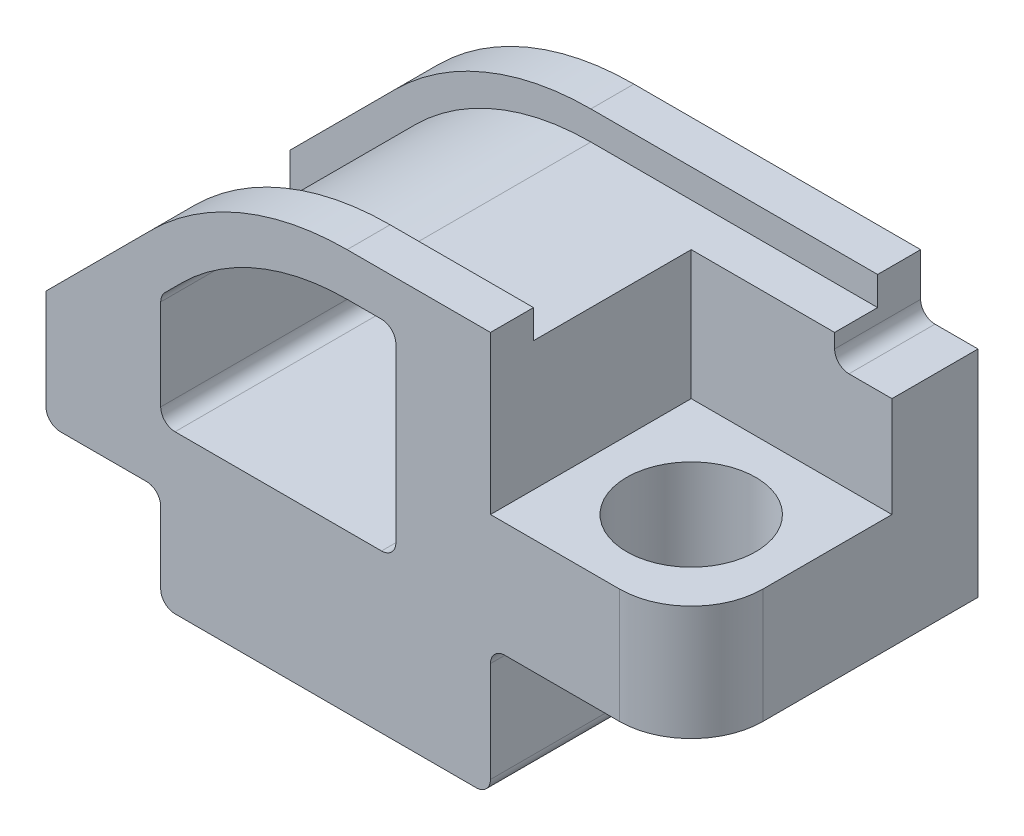
SolidWorks part; units mm, degrees
material "Copper"
ref_plane "Front Plane" through (0, 0, 0) normal (0, 0, 1) x (1, 0, 0)
ref_plane "Top Plane" through (0, 0, 0) normal (0, 1, 0) x (1, 0, 0)
ref_plane "Right Plane" through (0, 0, 0) normal (1, 0, 0) x (0, 0, -1)
sketch "Sketch1" plane through (0, 0, 0) normal (0, 0, 1) x (1, 0, 0)
  line L0 (0, 0) -> (-115, 0)
  line L1 (-115, 0) -> (-115, 35)
  line L2 (-115, 35) -> (-155, 35)
  line L3 (-155, 35) -> (-155, 75)
  line L5 (-50, 140) -> (50, 140)
  line L9 (70, 45) -> (0, 45)
  line L10 (0, 45) -> (0, 0)
  line L11 (-155, 75) -> (-118.2843, 111.7157)
  line L12 (70, 45) -> (70, 120)
  line L13 (70, 120) -> (50, 120)
  line L14 (50, 120) -> (50, 140)
  arc A0 (-50, 140) -> (-118.2843, 111.7157) centre (-50, 43.4315) ccw
  point P9 (60, 120)
  point P14 (17.1564, 142.4918)
  point P16 (-156.4116, 75)
  dimension "D1" = 115
  dimension "D2" = 35
  dimension "D3" = 40
  dimension "D4" = 45
  dimension "D8" = 70
  dimension "D9" = 45
  dimension "D5" = 100
  dimension "D6" = 20
  dimension "D7" = 75
  dimension "D10" = 140
  dimension "D11" = 225
extrude "Boss-Extrude1" add sketch "Sketch1" along normal mid plane 100
sketch "Sketch2" plane through (0, 0, 50) normal (0, 0, 1) x (1, 0, 0)
  line L0 (-33, 55) -> (-33, 125)
  line L1 (0, 0) -> (0, 45) construction
  line L17 (-115, 93.7868) -> (-115, 55)
  line L18 (-107.6777, 101.1091) -> (-144.3934, 64.3934)
  line L19 (-107.6777, 101.1091) -> (-115, 93.7868)
  line L20 (-115, 55) -> (-33, 55)
  line L24 (-115, 35) -> (-115, 0) construction
  line L25 (-50, 125) -> (-33, 125)
  arc A12 (-50, 125) -> (-107.6777, 101.1091) centre (-50, 43.4315) ccw
  arc A13 (-50, 125) -> (-107.6777, 101.1091) centre (-50, 43.4315) ccw
  dimension "D1" = 15
  dimension "D2" = 33
  dimension "D3" = 20
extrude "Cut-Extrude1" cut sketch "Sketch2" against normal through all both and the other way through all
sketch "Sketch3" plane through (0, 140, 0) normal (0, 1, 0) x (1, 0, 0)
  line L1 (70, -50) -> (0, -50)
  line L2 (70, -50) -> (70, 20)
  line L3 (70, 20) -> (0, 20)
  line L4 (0, -50) -> (0, 20)
  dimension "D1" = 70
extrude "Cut-Extrude2" cut sketch "Sketch3" against normal blind 55
sketch "Sketch4" plane through (0, 85, 0) normal (0, 1, 0) x (1, 0, 0)
  line L0 (70, -50) -> (70, 20) construction
  line L1 (0, -50) -> (70, -50) construction
  line L2 (35, -50) -> (35, 20) construction
  line L3 (70, 20) -> (0, 20) construction
  line L4 (70, -25) -> (70, -50)
  line L5 (70, -50) -> (45, -50)
  circle A0 centre (35, -15) radius 22.5
  arc A1 (45, -50) -> (70, -25) centre (45, -25) ccw
  point P5 (70, -15)
  dimension "D1" = 45
  dimension "D2" = 25
extrude "Cut-Extrude3" cut sketch "Sketch4" against normal through all
sketch "Sketch5" plane through (0, 0, 0) normal (0, 0, 1) x (1, 0, 0)
  line L6 (50, 140) -> (50, 120) construction
  line L7 (50, 140) -> (0, 140) construction
  line L8 (-118.2843, 111.7157) -> (-155, 75) construction
  line L9 (-145, 70.8579) -> (-145, 35)
  line L10 (-111.2132, 104.6447) -> (-145, 70.8579)
  line L11 (0, 130) -> (-50, 130)
  line L12 (50, 130) -> (0, 130)
  line L14 (-111.2132, 104.6447) -> (-155, 60.8579)
  line L15 (0, 130) -> (-50, 130)
  line L16 (50, 130) -> (0, 130)
  line L17 (50, 140) -> (50, 130)
  line L18 (50, 140) -> (0, 140)
  line L19 (-118.2843, 111.7157) -> (-155, 75)
  line L21 (0, 140) -> (-50, 140) construction
  line L22 (0, 140) -> (-50, 140)
  line L25 (-155, 75) -> (-155, 35) construction
  line L26 (-155, 75) -> (-155, 60.8579)
  arc A1 (-50, 140) -> (-118.2843, 111.7157) centre (-50, 43.4315) ccw construction
  arc A2 (-50, 130) -> (-111.2132, 104.6447) centre (-50, 43.4315) ccw
  arc A3 (-50, 130) -> (-111.2132, 104.6447) centre (-50, 43.4315) ccw
  arc A4 (-50, 140) -> (-118.2843, 111.7157) centre (-50, 43.4315) ccw
  point P1 (-155, 60.8302)
  dimension "D1" = 10
extrude "Cut-Extrude4" cut sketch "Sketch5" against normal mid plane 70
fillet "Fillet1" radius 5 4 edges at (-33, 55, 0) (-33, 125, 0) (-115, 93.7868, 0) (-115, 55, 0)
fillet "Fillet2" radius 5 6 edges at (50, 120, -35) (0, 45, 0) (0, 0, 0) (-155, 35, 0) (-115, 0, 0) (-115, 35, 0)
equation "\"A\"= 225"
equation "\"B\"= 40"
equation "\"C\"= 45"
equation "\"D\"= 45"
equation "\"D3@Sketch1\"=\"B\""
equation "\"D4@Sketch1\"=\"D\""
equation "\"D11@Sketch1\"=\"A\""
equation "\"D1@Sketch4\"=\"C\""
